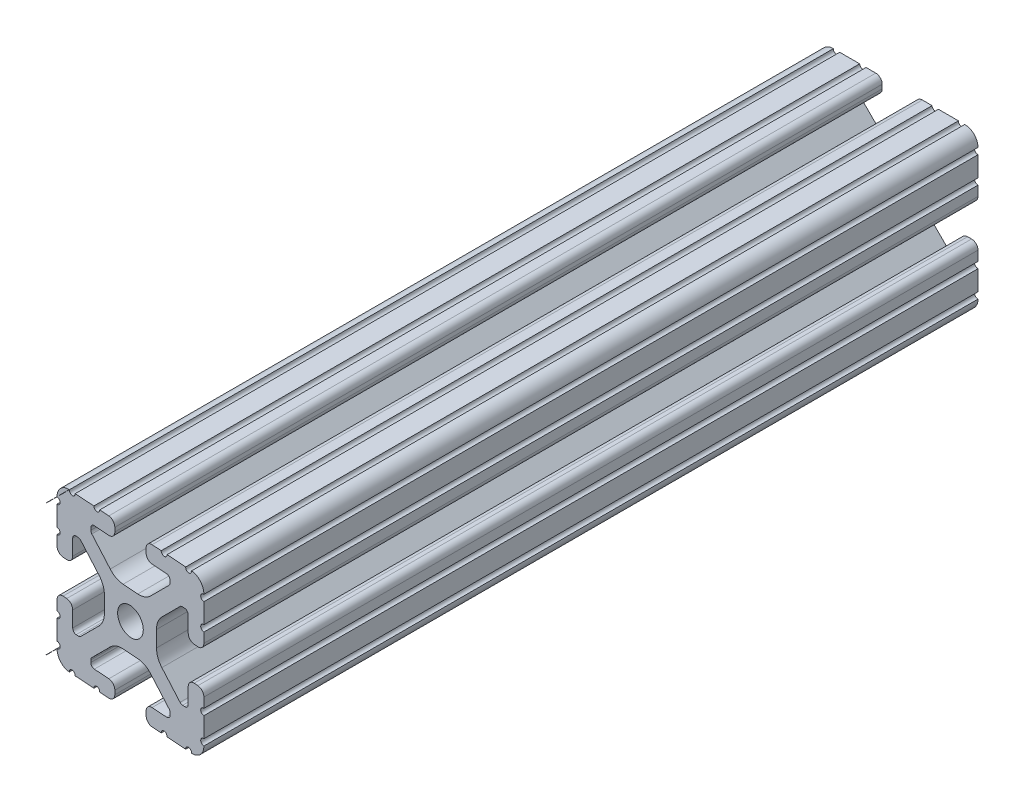
SolidWorks part; units mm, degrees
material "6061 Alloy"
ref_plane "Front Plane" through (0, 0, 0) normal (0, 0, 1) x (1, 0, 0)
ref_plane "Top Plane" through (0, 0, 0) normal (0, 1, 0) x (1, 0, 0)
ref_plane "Right Plane" through (0, 0, 0) normal (1, 0, 0) x (0, 0, -1)
sketch "Sketch1" plane through (0, 0, 0) normal (0, 0, 1) x (1, 0, 0)
  line L0 (0, 25.6181) -> (0, -24.623) construction
  line L1 (-20.8943, 0) -> (20.4607, 0) construction
  line L2 (-10.0229, 12.9148) -> (-5.2522, 8.144)
  line L3 (-10.287, 14.0843) -> (-10.287, 13.5524)
  line L4 (-5.6176, 14.986) -> (-9.3853, 14.986)
  line L5 (-4.064, 17.4964) -> (-4.064, 16.5396)
  line L6 (-7.9742, 19.05) -> (-5.6176, 19.05)
  line L7 (-14.3277, 19.05) -> (-9.4982, 19.05)
  line L8 (-19.05, 9.4961) -> (-19.05, 14.3277)
  line L9 (-19.05, 5.6176) -> (-19.05, 7.9763)
  line L10 (-16.5396, 4.064) -> (-17.4964, 4.064)
  line L11 (-14.986, 9.3853) -> (-14.986, 5.6176)
  line L12 (-13.516, 10.287) -> (-14.0843, 10.287)
  line L13 (-8.1476, 5.2921) -> (-12.8784, 10.0229)
  line L14 (-6.7564, -1.9335) -> (-6.7564, 1.9335)
  line L15 (-12.8784, -10.0229) -> (-8.1476, -5.2921)
  line L16 (-14.0843, -10.287) -> (-13.516, -10.287)
  line L17 (-14.986, -5.6176) -> (-14.986, -9.3853)
  line L18 (-17.4964, -4.064) -> (-16.5396, -4.064)
  line L19 (-19.05, -7.9763) -> (-19.05, -5.6176)
  line L20 (-19.05, -14.3277) -> (-19.05, -9.4961)
  line L21 (-9.4961, -19.05) -> (-14.3277, -19.05)
  line L22 (-5.6176, -19.05) -> (-7.9763, -19.05)
  line L23 (-4.064, -17.4964) -> (-4.064, -16.5396)
  line L24 (10.0229, -12.9148) -> (5.2522, -8.144)
  line L25 (10.287, -14.0843) -> (10.287, -13.5524)
  line L26 (5.6176, -14.986) -> (9.3853, -14.986)
  line L28 (-1.9022, 6.7564) -> (1.9022, 6.7564)
  line L29 (-1.9022, -6.7564) -> (1.9022, -6.7564)
  line L31 (-5.6176, -14.986) -> (-9.3853, -14.986)
  line L32 (-10.287, -14.0843) -> (-10.287, -13.5524)
  line L33 (-10.0229, -12.9148) -> (-5.2522, -8.144)
  line L66 (4.064, -16.5396) -> (4.064, -17.4964)
  line L67 (5.6176, -19.05) -> (7.9763, -19.05)
  line L68 (9.4961, -19.05) -> (14.3277, -19.05)
  line L69 (19.05, -14.3277) -> (19.05, -9.4961)
  line L70 (19.05, -7.9763) -> (19.05, -5.6176)
  line L71 (17.4964, -4.064) -> (16.5396, -4.064)
  line L72 (14.986, -5.6176) -> (14.986, -9.3853)
  line L73 (14.0843, -10.287) -> (13.516, -10.287)
  line L74 (12.8784, -10.0229) -> (8.1476, -5.2921)
  line L75 (6.7564, -1.9335) -> (6.7564, 1.9335)
  line L76 (8.1476, 5.2921) -> (12.8784, 10.0229)
  line L77 (13.516, 10.287) -> (14.0843, 10.287)
  line L78 (14.986, 9.3853) -> (14.986, 5.6176)
  line L79 (16.5396, 4.064) -> (17.4964, 4.064)
  line L80 (19.05, 5.6176) -> (19.05, 7.9763)
  line L81 (19.05, 9.4961) -> (19.05, 14.3277)
  line L82 (14.3277, 19.05) -> (9.4982, 19.05)
  line L83 (7.9742, 19.05) -> (5.6176, 19.05)
  line L84 (4.064, 17.4964) -> (4.064, 16.5396)
  line L85 (5.6176, 14.986) -> (9.3853, 14.986)
  line L86 (10.287, 14.0843) -> (10.287, 13.5524)
  line L87 (10.0229, 12.9148) -> (5.2522, 8.144)
  arc A0 (-10.0229, 12.9148) -> (-10.287, 13.5524) centre (-9.3853, 13.5524) cw
  circle A1 centre (0, 0) radius 3.3274
  arc A2 (-10.287, 14.0843) -> (-9.3853, 14.986) centre (-9.3853, 14.0843) cw
  arc A3 (-4.064, 16.5396) -> (-5.6176, 14.986) centre (-5.6176, 16.5396) cw
  arc A4 (-5.6176, 19.05) -> (-4.064, 17.4964) centre (-5.6176, 17.4964) cw
  arc A5 (-7.9742, 19.05) -> (-9.4982, 19.05) centre (-8.7362, 19.05) cw
  arc A6 (-14.3277, 19.05) -> (-15.8475, 19.05) centre (-15.0876, 18.9933) cw
  arc A7 (-19.05, 15.8475) -> (-15.8475, 19.05) centre (-15.8751, 15.8751) cw
  arc A8 (-19.05, 15.8475) -> (-19.05, 14.3277) centre (-18.9933, 15.0876) cw
  arc A9 (-19.05, 9.4961) -> (-19.05, 7.9763) centre (-18.9933, 8.7362) cw
  arc A10 (-17.4964, 4.064) -> (-19.05, 5.6176) centre (-17.4964, 5.6176) cw
  arc A11 (-14.986, 5.6176) -> (-16.5396, 4.064) centre (-16.5396, 5.6176) cw
  arc A12 (-14.986, 9.3853) -> (-14.0843, 10.287) centre (-14.0843, 9.3853) cw
  arc A13 (-13.516, 10.287) -> (-12.8784, 10.0229) centre (-13.516, 9.3853) cw
  arc A14 (-8.1476, 5.2921) -> (-6.7564, 1.9335) centre (-11.5062, 1.9335) cw
  arc A15 (-6.7564, -1.9335) -> (-8.1476, -5.2921) centre (-11.5062, -1.9335) cw
  arc A16 (-12.8784, -10.0229) -> (-13.516, -10.287) centre (-13.516, -9.3853) cw
  arc A17 (-14.0843, -10.287) -> (-14.986, -9.3853) centre (-14.0843, -9.3853) cw
  arc A18 (-16.5396, -4.064) -> (-14.986, -5.6176) centre (-16.5396, -5.6176) cw
  arc A19 (-19.05, -5.6176) -> (-17.4964, -4.064) centre (-17.4964, -5.6176) cw
  arc A20 (-19.05, -7.9763) -> (-19.05, -9.4961) centre (-18.9933, -8.7362) cw
  arc A21 (-19.05, -14.3277) -> (-19.05, -15.8475) centre (-18.9933, -15.0876) cw
  arc A22 (-15.8475, -19.05) -> (-19.05, -15.8475) centre (-15.8751, -15.8751) cw
  arc A23 (-15.8475, -19.05) -> (-14.3277, -19.05) centre (-15.0876, -18.9933) cw
  arc A24 (-9.4961, -19.05) -> (-7.9763, -19.05) centre (-8.7362, -18.9933) cw
  arc A25 (-4.064, -17.4964) -> (-5.6176, -19.05) centre (-5.6176, -17.4964) cw
  arc A26 (-5.2522, -8.144) -> (-1.9022, -6.7564) centre (-1.9022, -11.494) cw
  arc A27 (1.9022, -6.7564) -> (5.2522, -8.144) centre (1.9022, -11.494) cw
  arc A28 (10.0229, -12.9148) -> (10.287, -13.5524) centre (9.3853, -13.5524) cw
  arc A29 (10.287, -14.0843) -> (9.3853, -14.986) centre (9.3853, -14.0843) cw
  arc A30 (4.064, -16.5396) -> (5.6176, -14.986) centre (5.6176, -16.5396) cw
  arc A31 (-4.064, -16.5396) -> (-5.6176, -14.986) centre (-5.6176, -16.5396) ccw
  arc A32 (-10.287, -14.0843) -> (-9.3853, -14.986) centre (-9.3853, -14.0843) ccw
  arc A33 (-10.0229, -12.9148) -> (-10.287, -13.5524) centre (-9.3853, -13.5524) ccw
  arc A79 (4.064, -17.4964) -> (5.6176, -19.05) centre (5.6176, -17.4964) ccw
  arc A80 (9.4961, -19.05) -> (7.9763, -19.05) centre (8.7362, -18.9933) ccw
  arc A81 (15.8475, -19.05) -> (14.3277, -19.05) centre (15.0876, -18.9933) ccw
  arc A82 (15.8475, -19.05) -> (19.05, -15.8475) centre (15.8751, -15.8751) ccw
  arc A83 (19.05, -14.3277) -> (19.05, -15.8475) centre (18.9933, -15.0876) ccw
  arc A84 (19.05, -7.9763) -> (19.05, -9.4961) centre (18.9933, -8.7362) ccw
  arc A85 (19.05, -5.6176) -> (17.4964, -4.064) centre (17.4964, -5.6176) ccw
  arc A86 (16.5396, -4.064) -> (14.986, -5.6176) centre (16.5396, -5.6176) ccw
  arc A87 (14.0843, -10.287) -> (14.986, -9.3853) centre (14.0843, -9.3853) ccw
  arc A88 (12.8784, -10.0229) -> (13.516, -10.287) centre (13.516, -9.3853) ccw
  arc A89 (6.7564, -1.9335) -> (8.1476, -5.2921) centre (11.5062, -1.9335) ccw
  arc A90 (8.1476, 5.2921) -> (6.7564, 1.9335) centre (11.5062, 1.9335) ccw
  arc A91 (13.516, 10.287) -> (12.8784, 10.0229) centre (13.516, 9.3853) ccw
  arc A92 (14.986, 9.3853) -> (14.0843, 10.287) centre (14.0843, 9.3853) ccw
  arc A93 (14.986, 5.6176) -> (16.5396, 4.064) centre (16.5396, 5.6176) ccw
  arc A94 (17.4964, 4.064) -> (19.05, 5.6176) centre (17.4964, 5.6176) ccw
  arc A95 (19.05, 9.4961) -> (19.05, 7.9763) centre (18.9933, 8.7362) ccw
  arc A96 (19.05, 15.8475) -> (19.05, 14.3277) centre (18.9933, 15.0876) ccw
  arc A97 (19.05, 15.8475) -> (15.8475, 19.05) centre (15.8751, 15.8751) ccw
  arc A98 (14.3277, 19.05) -> (15.8475, 19.05) centre (15.0876, 18.9933) ccw
  arc A99 (7.9742, 19.05) -> (9.4982, 19.05) centre (8.7362, 19.05) ccw
  arc A100 (5.6176, 19.05) -> (4.064, 17.4964) centre (5.6176, 17.4964) ccw
  arc A101 (4.064, 16.5396) -> (5.6176, 14.986) centre (5.6176, 16.5396) ccw
  arc A102 (10.287, 14.0843) -> (9.3853, 14.986) centre (9.3853, 14.0843) ccw
  arc A103 (10.0229, 12.9148) -> (10.287, 13.5524) centre (9.3853, 13.5524) ccw
  arc A104 (1.9022, 6.7564) -> (5.2522, 8.144) centre (1.9022, 11.494) ccw
  arc A105 (-5.2522, 8.144) -> (-1.9022, 6.7564) centre (-1.9022, 11.494) ccw
  dimension "D1" = 6.6548
  dimension "D2" = 19.05
  dimension "D3" = 38.1
  dimension "D4" = 20.574
  dimension "D5" = 13.5128
  dimension "D6" = 4.064
  dimension "D7" = 8.128
  dimension "D8" = 4.064
  dimension "D9" = 12.2936
extrude "Extrude1" add sketch "Sketch1" against normal blind 186.817
sketch "Sketch2" plane through (0, 19.05, 0) normal (0, 1, 0) x (1, 0, 0)
  line L0 (19.05, 0) -> (-19.05, 2.6642)
  line L1 (-19.05, 186.817) -> (-19.05, 0) construction
  line L2 (-19.05, 2.6642) -> (-19.05, 0)
  line L3 (-19.05, 0) -> (19.05, 0)
  dimension "D1" = 4
extrude "Cut-Extrude1" cut sketch "Sketch2" against normal through all
